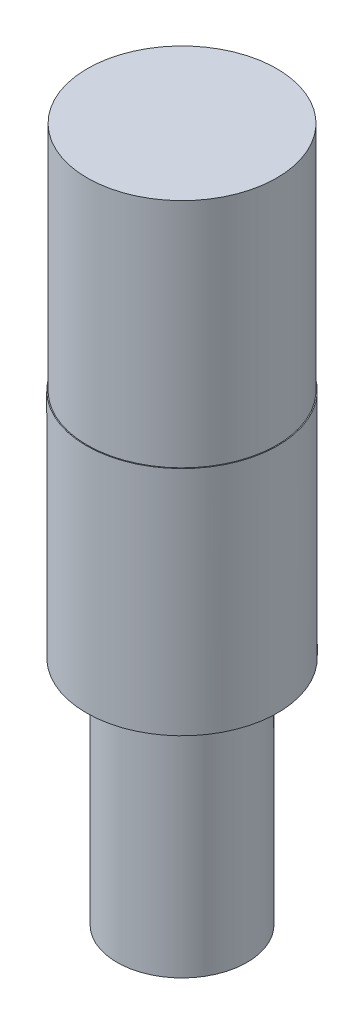
SolidWorks part; units mm, degrees
material "PUR"
ref_plane "Z" through (0, 0, 0) normal (0, 0, 1) x (1, 0, 0)
ref_plane "Y" through (0, 0, 0) normal (0, 1, 0) x (1, 0, 0)
ref_plane "X" through (0, 0, 0) normal (1, 0, 0) x (0, 0, -1)
sketch "Sketch1" plane through (0, 0, 0) normal (0, 1, 0) x (1, 0, 0)
  circle A0 centre (0, 0) radius 5.5562
  dimension "D1" = 11.1125
extrude "Boss-Extrude1" add sketch "Sketch1" along normal blind 38.1
sketch "Sketch2" plane through (0, 38.1, 0) normal (0, 1, 0) x (1, 0, 0)
  circle A0 centre (0, 0) radius 5.2
  circle A1 centre (0, 0) radius 6.633
  dimension "D1" = 10.4
extrude "Cut-Extrude1" cut sketch "Sketch2" against normal blind 12.7
sketch "Sketch3" plane through (0, 25.4, 0) normal (0, 1, 0) x (1, 0, 0)
  circle A0 centre (0, 0) radius 5.25
  circle A1 centre (0, 0) radius 7.2483
  dimension "D1" = 10.5
extrude "Cut-Extrude2" cut sketch "Sketch3" against normal blind 12.7
sketch "Sketch4" plane through (0, 0, 0) normal (0, -1, 0) x (1, 0, 0)
  circle A0 centre (0, 0) radius 3.5687
  circle A1 centre (0, 0) radius 6.5211
  dimension "D1" = 7.1374
extrude "Cut-Extrude3" cut sketch "Sketch4" against normal blind 12.7
